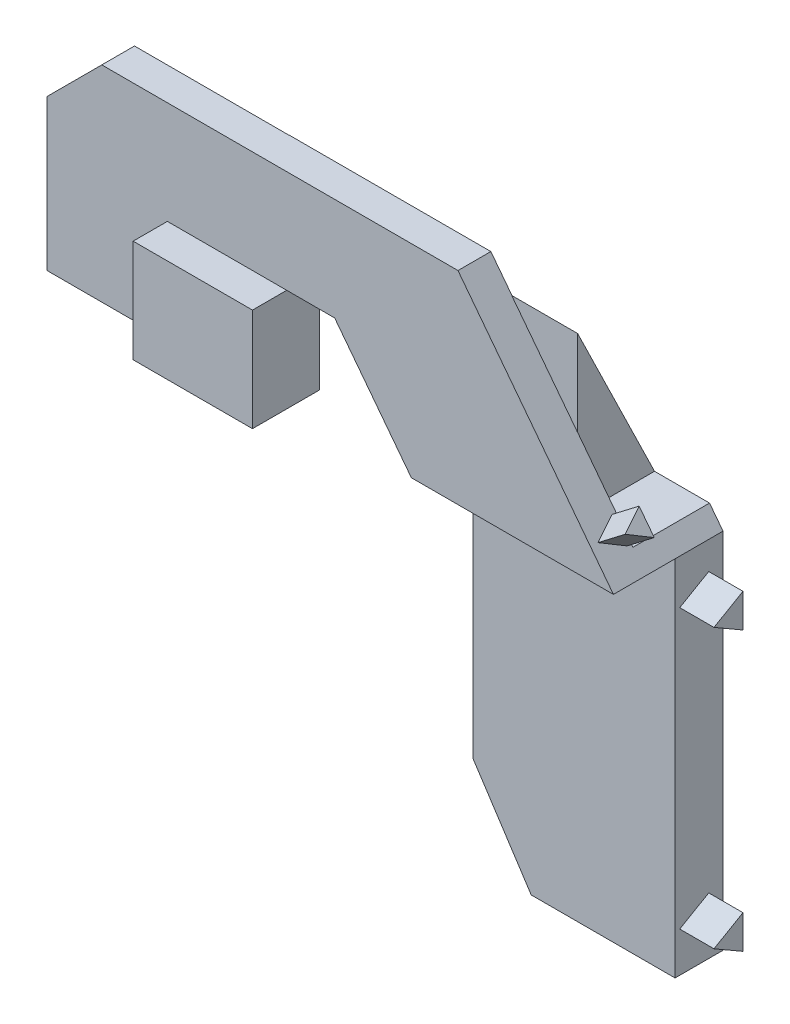
SolidWorks part; units mm, degrees
ref_plane "Ön Düzlem" through (0, 0, 0) normal (0, 0, 1) x (1, 0, 0)
ref_plane "Üst Düzlem" through (0, 0, 0) normal (0, 1, 0) x (1, 0, 0)
ref_plane "Sağ Düzlem" through (0, 0, 0) normal (1, 0, 0) x (0, 0, -1)
sketch "Çizim1" plane through (0, 0, 0) normal (0, 0, 1) x (1, 0, 0)
  line L0 (0, 0) -> (35, 0)
  line L1 (0, 0) -> (0, 22)
  line L2 (8, 30) -> (60, 30)
  line L3 (0, 22) -> (8, 30)
  line L4 (82.6951, 0.3976) -> (60, 30)
  line L5 (35, 0) -> (35, 15)
  line L6 (35, 15) -> (42, 15)
  line L7 (42, 15) -> (53.1951, 0.3976)
  line L8 (53.1951, 0.3976) -> (82.6951, 0.3976)
  line L9 (53.1951, 0.3976) -> (82.6951, 0.3976)
  line L10 (53.1951, 0.3976) -> (53.1951, -39.6024)
  line L11 (82.6951, 0.3976) -> (82.6951, -52.6024)
  line L12 (61.6951, -52.6024) -> (82.6951, -52.6024)
  line L13 (61.6951, -52.6024) -> (53.1951, -39.6024)
  point P4 (0, 30)
  dimension "D1" = 37.3011
  dimension "D2" = 30
  dimension "D3" = 60
  dimension "D4" = 35
  dimension "D5" = 15
  dimension "D7" = 7
  dimension "D8" = 18.4
  dimension "D9" = 53
  dimension "D10" = 8.5
  dimension "D11" = 13
extrude "Yükseklik-Ekstrüzyon1" add sketch "Çizim1" along normal blind 7 contours L7 L8 L4 L2 L3 L1 L0 L5 L6 | L13 L12 L11 L8 L10
sketch "Çizim2" plane through (0, 0, 0) normal (0, 0, -1) x (-1, 0, 0)
  line L0 (-53.1951, 0.3976) -> (-82.6951, 0.3976)
  line L13 (-53.1951, 0.3976) -> (-42, 15)
  line L14 (-42, 15) -> (-35, 15)
  line L15 (-35, 15) -> (-35, 0)
  line L16 (-35, 0) -> (0, 0)
  line L17 (0, 0) -> (0, 22)
  line L18 (0, 22) -> (-8, 30)
  line L19 (-8, 30) -> (-60, 30)
  line L20 (-60, 30) -> (-82.6951, 0.3976)
  line L21 (-82.6951, 0.3976) -> (-82.6951, -52.6024)
  line L22 (-82.6951, -52.6024) -> (-61.6951, -52.6024)
  line L23 (-61.6951, -52.6024) -> (-53.1951, -39.6024)
  line L24 (-53.1951, -39.6024) -> (-53.1951, 0.3976)
  line L25 (-53.1951, 0.3976) -> (-42, 15)
  line L26 (-42, 15) -> (-35, 15)
  line L27 (-35, 15) -> (-35, 0)
  line L28 (-35, 0) -> (0, 0)
  line L29 (0, 0) -> (0, 22)
  line L30 (0, 22) -> (-8, 30)
  line L31 (-8, 30) -> (-60, 30)
  line L32 (-60, 30) -> (-82.6951, 0.3976)
  dimension "D1" = 0
extrude "Yükseklik-Ekstrüzyon3" add sketch "Çizim2" against normal blind 16
sketch "Çizim4" plane through (0, 0, 0) normal (0, -1, 0) x (1, 0, 0)
  line L0 (35, 11.2265) -> (6.0453, 11.2265)
  line L1 (35, 11.2265) -> (35, 0)
  line L2 (6.0453, 11.2265) -> (6.0453, 0)
  line L3 (35, 0) -> (6.0453, 0)
  line L4 (35, 16) -> (35, 0) construction
  line L5 (0, 0) -> (35, 0) construction
extrude "Kes-Ekstrüzyon1" cut sketch "Çizim4" against normal blind 46
sketch "Çizim5" plane through (-11, 11, 0) normal (-0.7071, 0.7071, 0) x (0, 0, 1)
  line L0 (11.2265, 24.1056) -> (11.2265, 15.5563)
  line L1 (11.2265, 24.1056) -> (0.1958, 24.1056)
  line L2 (11.2265, 15.5563) -> (0.1958, 15.5563)
  line L3 (0.1958, 24.1056) -> (0.1958, 15.5563)
  line L4 (16, 15.5563) -> (0, 15.5563) construction
extrude "Kes-Ekstrüzyon2" cut sketch "Çizim5" against normal blind 46
sketch "Çizim6" plane through (0, 0, 0) normal (0, -1, 0) x (1, 0, 0)
  line L0 (6.0453, 8) -> (0, 8)
  line L1 (6.0453, 8) -> (6.0453, -2.2924)
  line L2 (0, 8) -> (0, -2.2924)
  line L3 (6.0453, -2.2924) -> (0, -2.2924)
  line L4 (6.0453, 11.2265) -> (6.0453, 0) construction
  line L5 (0, 16) -> (0, 0) construction
  line L6 (0, 0) -> (6.0453, 0) construction
extrude "Kes-Ekstrüzyon3" cut sketch "Çizim6" against normal blind 46
sketch "Çizim7" plane through (0, 0, 0) normal (-1, 0, 0) x (0, 0, 1)
  line L0 (11.2265, 22) -> (8, 22)
  line L1 (11.2265, 22) -> (11.2265, 6.9803)
  line L2 (8, 22) -> (8, 6.9803)
  line L3 (11.2265, 6.9803) -> (8, 6.9803)
extrude "Kes-Ekstrüzyon5" cut sketch "Çizim7" against normal blind 10
sketch "Çizim9" plane through (35, 0, 0) normal (-1, 0, 0) x (0, 0, 1)
  line L0 (11.2265, 15) -> (11.2265, 30)
  line L1 (11.2265, 15) -> (0, 15)
  line L2 (11.2265, 30) -> (0, 30)
  line L3 (0, 15) -> (0, 30)
extrude "Kes-Ekstrüzyon6" cut sketch "Çizim9" against normal blind 50
sketch "Çizim11" plane through (0, 0, 0) normal (0, 0, -1) x (-1, 0, 0)
  line L0 (-80.7274, 2.9643) -> (-71.5, 15)
  line L1 (-80.7274, 2.9643) -> (-51.2274, 2.9643)
  line L2 (-71.5, 15) -> (-42, 15)
  line L3 (-51.2274, 2.9643) -> (-42, 15)
  line L4 (-82.6951, 0.3976) -> (-71.5, 15) construction
extrude "Kes-Ekstrüzyon9" cut sketch "Çizim11" against normal blind 11.2
sketch "Çizim14" plane through (82.6951, 0, 0) normal (1, 0, 0) x (0, 0, -1)
  line L0 (0, 0.3976) -> (0, -52.6024) construction
  line L1 (-2.0826, -49.1958) -> (-2.0826, -44.3034)
  line L2 (-2.0826, -44.3034) -> (-6.3195, -46.7496)
  line L3 (-6.3195, -46.7496) -> (-2.0826, -49.1958)
  line L4 (-3.4949, -46.7496) -> (-3.4949, 49953.2504) construction
  line L6 (-2.0826, -3.6696) -> (-6.3195, -6.1158)
  line L7 (-6.3195, -6.1158) -> (-2.0826, -8.562)
  line L8 (-2.0826, -8.562) -> (-2.0826, -3.6696)
  circle A0 centre (-3.4949, -46.7496) radius 1.4123 construction
  circle A1 centre (-3.4949, -6.1158) radius 1.4123 construction
extrude "Yükseklik-Ekstrüzyon4" add sketch "Çizim14" along normal blind 5
sketch "Çizim15" plane through (52.2743, 40.077, 0) normal (0.7936, 0.6084, 0) x (0, 0, -1)
  line L0 (-11.2, -31.5988) -> (-11.2, -46.7646) construction
  line L1 (-14.921, -44.5273) -> (-11.7811, -46.3402)
  line L2 (-11.7811, -46.3402) -> (-11.7811, -42.7145)
  line L3 (-11.7811, -42.7145) -> (-14.921, -44.5273)
  circle A0 centre (-12.8277, -44.5273) radius 1.0466 construction
extrude "Yükseklik-Ekstrüzyon7" add sketch "Çizim15" along normal blind 5
sketch "Çizim17" plane through (0, 0, 16) normal (0, 0, 1) x (1, 0, 0)
  line L0 (35, 15) -> (35, 0)
  line L1 (35, 15) -> (17.5731, 15)
  line L2 (35, 0) -> (17.5731, 0)
  line L3 (17.5731, 15) -> (17.5731, 0)
extrude "Yükseklik-Ekstrüzyon8" add sketch "Çizim17" along normal blind 5
sketch "Çizim18" plane through (82.6951, 0, 0) normal (1, 0, 0) x (0, 0, -1)
  line L0 (0, 2.9643) -> (-11.2265, 26)
  line L1 (-11.2265, 22) -> (-11.2265, 30) construction
  line L2 (-11.2, 2.9643) -> (0, 2.9643) construction
  line L3 (0, 2.9643) -> (-11.2, 2.9643)
  line L4 (-11.2, 2.9643) -> (0, 2.9643) construction
  line L5 (-11.2265, 26) -> (-11.2, 2.9643)
sketch "Çizim21" plane through (0, 0, 11.2265) normal (0, 0, -1) x (-1, 0, 0)
  line L0 (-42, 15) -> (-71.5, 15)
  line L1 (-42, 15) -> (-30.5, 30)
  line L2 (-71.5, 15) -> (-60, 30)
  line L3 (-30.5, 30) -> (-60, 30)
extrude "Yükseklik-Ekstrüzyon18" add sketch "Çizim21" along normal blind 0.028
extrude "Yükseklik-Ekstrüzyon20" add sketch "Çizim18" against normal blind 20 from offset 10
